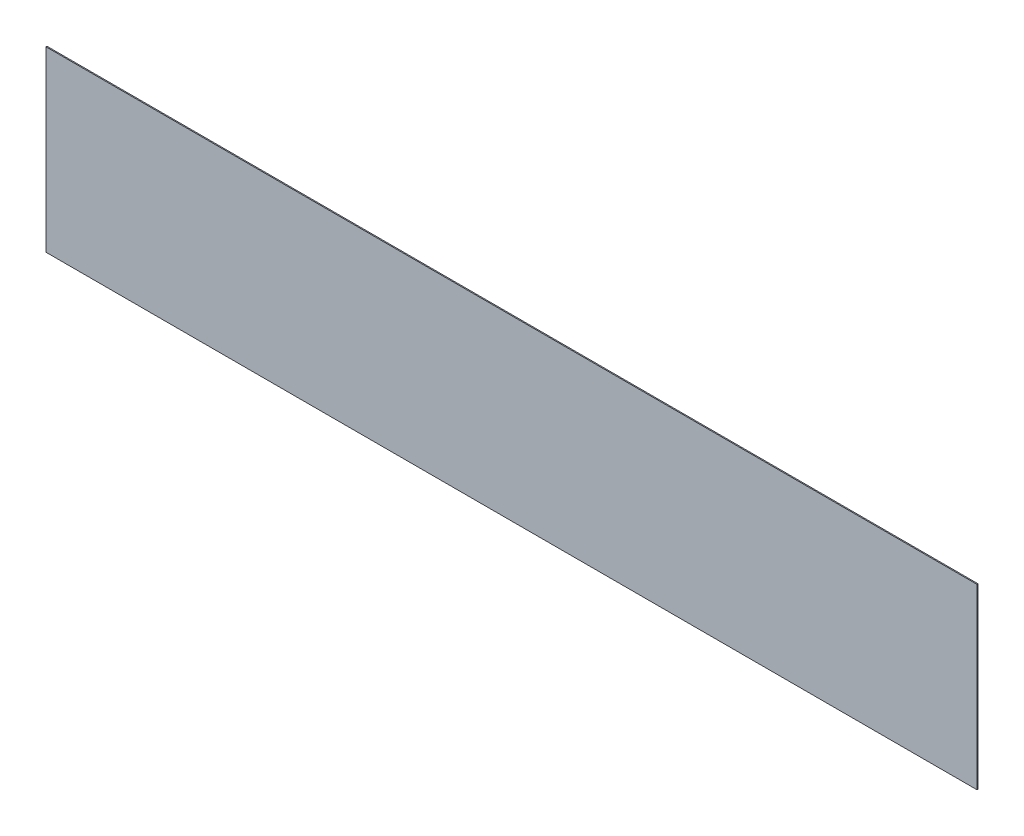
SolidWorks part; units mm, degrees
ref_plane "Front Plane" through (0, 0, 0) normal (0, 0, 1) x (1, 0, 0)
ref_plane "Top Plane" through (0, 0, 0) normal (0, 1, 0) x (1, 0, 0)
ref_plane "Right Plane" through (0, 0, 0) normal (1, 0, 0) x (0, 0, -1)
sketch "Sketch1" plane through (0, 0, 0) normal (0, 0, 1) x (1, 0, 0)
  line L0 (-237, -530.24) -> (213, -530.24) construction
  line L1 (213, -444.24) -> (213, -530.24) construction
  line L2 (-237, -444.24) -> (213, -444.24) construction
  line L3 (-237, -444.24) -> (-237, -530.24) construction
  line L4 (-237, -530.24) -> (213, -530.24)
  line L5 (213, -444.24) -> (213, -530.24)
  line L6 (-237, -444.24) -> (213, -444.24)
  line L7 (-237, -444.24) -> (-237, -530.24)
extrude "Boss-Extrude1" add sketch "Sketch1" along normal blind 0.5
